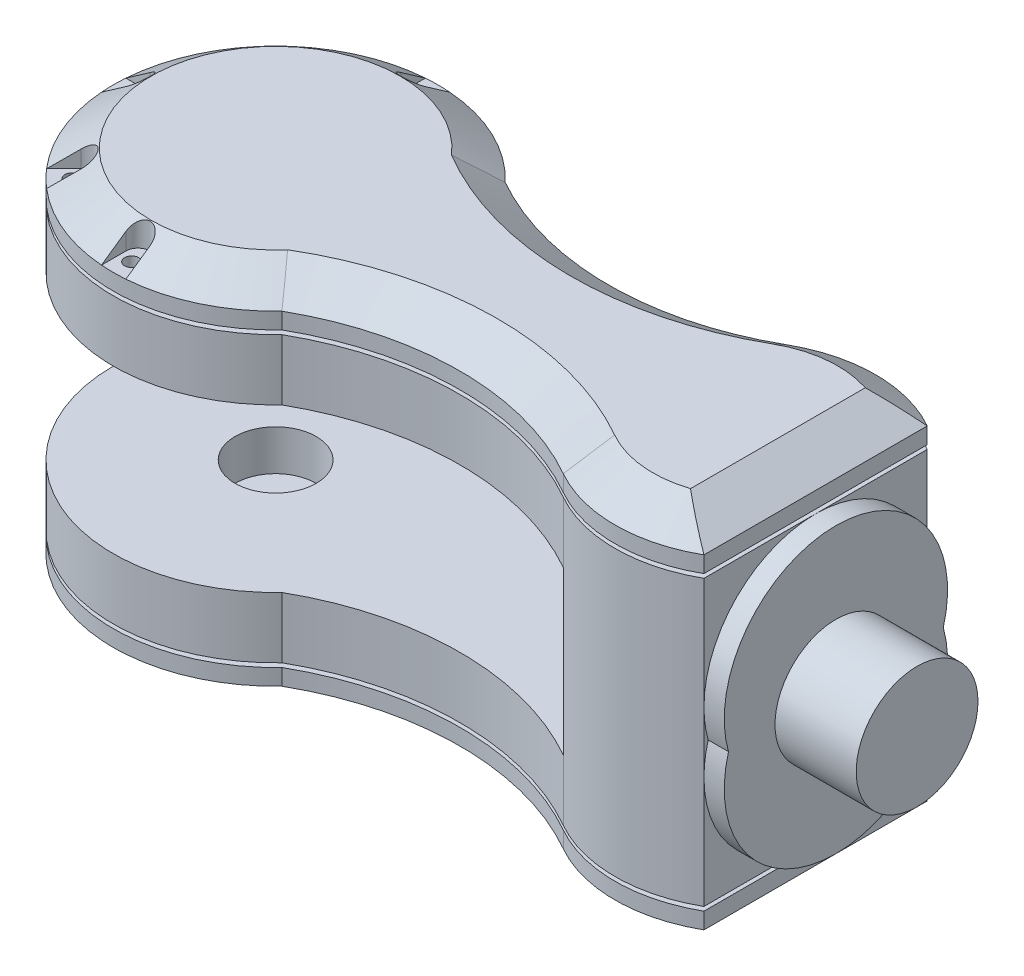
SolidWorks part; units mm, degrees
ref_plane "Front Plane" through (0, 0, 0) normal (1, 0, 0) x (0, 1, 0)
ref_plane "Top Plane" through (0, 0, 0) normal (0, 0, 1) x (0, 1, 0)
ref_plane "Right Plane" through (0, 0, 0) normal (0, 1, 0) x (-1, 0, 0)
sketch "Sketch1" plane through (0, 0, 0) normal (1, 0, 0) x (0, 1, 0)
  circle A0 centre (0, 0) radius 27.5
  dimension "D1" = 55
extrude "Boss-Extrude1" add sketch "Sketch1" against normal blind 5
ref_plane "Plane1" through (0, 27.5, 0) normal (0, 1, 0) x (-1, 0, 0)
sketch "Sketch3" plane through (0, 27.5, 0) normal (0, 1, 0) x (-1, 0, 0)
  line L0 (5, 0) -> (28, 0) construction
  line L1 (5, -27.5) -> (5, 27.5) construction
  line L2 (5, 27.5) -> (5, -27.5)
  arc A0 (5, 27.5) -> (39.6509, 27.5) centre (22.3254, -2.911) cw
  arc A1 (39.6509, 27.5) -> (108.9526, 27.5) centre (74.3017, 88.322) ccw
  arc A2 (5, -27.5) -> (39.6509, -27.5) centre (22.3254, 2.911) ccw
  arc A3 (39.6509, -27.5) -> (108.9526, -27.5) centre (74.3017, -88.322) cw
  arc A4 (108.9526, -27.5) -> (108.9526, 27.5) centre (138, 0) ccw
  dimension "D2" = 70
  dimension "D3" = 80
  dimension "D5" = 35
  dimension "D1" = 23
  dimension "D4" = 110
extrude "Boss-Extrude2" add sketch "Sketch3" along normal blind 15 separate body
sketch "Sketch7" plane through (0, 42.5, 0) normal (0, 1, 0) x (-1, 0, 0)
  line L2 (7.5, 26.0106) -> (7.5, -26.0106)
  line L3 (7.5, 26.0106) -> (7.5, -26.0106)
  arc A10 (38.4133, 25.3278) -> (7.5, 26.0106) centre (22.3254, -2.911) ccw
  arc A11 (7.5, -26.0106) -> (38.4133, -25.3278) centre (22.3254, 2.911) ccw
  arc A12 (110.5204, -25.5171) -> (38.4133, -25.3278) centre (74.3017, -88.322) ccw
  arc A13 (110.5204, -25.5171) -> (110.5204, 25.5171) centre (138, 0) ccw
  arc A14 (38.4133, 25.3278) -> (110.5204, 25.5171) centre (74.3017, 88.322) ccw
  arc A15 (38.4133, 25.3278) -> (7.5, 26.0106) centre (22.3254, -2.911) ccw
  arc A16 (7.5, -26.0106) -> (38.4133, -25.3278) centre (22.3254, 2.911) ccw
  arc A17 (110.5204, -25.5171) -> (38.4133, -25.3278) centre (74.3017, -88.322) ccw
  arc A18 (110.5204, -25.5171) -> (110.5204, 25.5171) centre (138, 0) ccw
  arc A19 (38.4133, 25.3278) -> (110.5204, 25.5171) centre (74.3017, 88.322) ccw
  dimension "D1" = 2.5
extrude "Boss-Extrude10" add sketch "Sketch7" along normal blind 1 contours A15 L3 A16 A17 A18 A19
sketch "Sketch18" plane through (0, 43.5, 0) normal (0, 1, 0) x (-1, 0, 0)
  line L1 (5, 27.5) -> (5, -27.5)
  line L2 (5, 27.5) -> (5, -27.5)
  arc A5 (39.6509, 27.5) -> (5, 27.5) centre (22.3254, -2.911) ccw
  arc A6 (5, -27.5) -> (39.6509, -27.5) centre (22.3254, 2.911) ccw
  arc A7 (108.9526, -27.5) -> (39.6509, -27.5) centre (74.3017, -88.322) ccw
  arc A8 (108.9526, -27.5) -> (108.9526, 27.5) centre (138, 0) ccw
  arc A9 (39.6509, 27.5) -> (108.9526, 27.5) centre (74.3017, 88.322) ccw
  arc A10 (39.6509, 27.5) -> (5, 27.5) centre (22.3254, -2.911) ccw
  arc A11 (5, -27.5) -> (39.6509, -27.5) centre (22.3254, 2.911) ccw
  arc A12 (108.9526, -27.5) -> (39.6509, -27.5) centre (74.3017, -88.322) ccw
  arc A13 (108.9526, -27.5) -> (108.9526, 27.5) centre (138, 0) ccw
  arc A14 (39.6509, 27.5) -> (108.9526, 27.5) centre (74.3017, 88.322) ccw
  dimension "D1" = 0
extrude "Boss-Extrude14" add sketch "Sketch18" along normal blind 4
sketch "Sketch19" plane through (0, 47.5, 0) normal (0, 1, 0) x (-1, 0, 0)
  line L1 (5, 27.5) -> (5, -27.5)
  line L2 (5, 27.5) -> (5, -27.5)
  arc A5 (39.6509, 27.5) -> (108.9526, 27.5) centre (74.3017, 88.322) ccw
  arc A6 (39.6509, 27.5) -> (5, 27.5) centre (22.3254, -2.911) ccw
  arc A7 (5, -27.5) -> (39.6509, -27.5) centre (22.3254, 2.911) ccw
  arc A8 (108.9526, -27.5) -> (39.6509, -27.5) centre (74.3017, -88.322) ccw
  arc A9 (108.9526, -27.5) -> (108.9526, 27.5) centre (138, 0) ccw
  arc A10 (39.6509, 27.5) -> (108.9526, 27.5) centre (74.3017, 88.322) ccw
  arc A11 (39.6509, 27.5) -> (5, 27.5) centre (22.3254, -2.911) ccw
  arc A12 (5, -27.5) -> (39.6509, -27.5) centre (22.3254, 2.911) ccw
  arc A13 (108.9526, -27.5) -> (39.6509, -27.5) centre (74.3017, -88.322) ccw
  arc A14 (108.9526, -27.5) -> (108.9526, 27.5) centre (138, 0) ccw
  dimension "D1" = 0
extrude "Boss-Extrude15" add sketch "Sketch19" along normal blind 6.5 draft 55
sketch "Sketch20" plane through (0, 54, 0) normal (0, 1, 0) x (-1, 0, 0)
  line L0 (5, 0) -> (178, 0) construction
  line L1 (5, 27.5) -> (5, -27.5) construction
  line L2 (177.8873, 3) -> (171.8873, 3)
  line L3 (177.8873, -3) -> (171.8873, -3)
  arc A0 (108.9526, -27.5) -> (108.9526, 27.5) centre (138, 0) ccw construction
  arc A1 (171.8873, 3) -> (171.8873, -3) centre (171.8873, 0) ccw
  arc A2 (177.8873, 3) -> (177.8873, -3) centre (173.8873, 0) cw
  dimension "D3" = 3
  dimension "D4" = 5
  dimension "D1" = 3
  dimension "D2" = 6
extrude "Cut-Extrude1" cut sketch "Sketch20" against normal blind 6.5
sketch "Sketch21" plane through (0, 47.5, 0) normal (0, 1, 0) x (-1, 0, 0)
  line L0 (178, 0) -> (168.8873, 0) construction
  arc A0 (177.8873, -3) -> (177.8873, 3) centre (138, 0) ccw construction
  arc A1 (171.8873, 3) -> (171.8873, -3) centre (171.8873, 0) ccw construction
  circle A2 centre (173.4437, 0) radius 1.75
  dimension "D1" = 3.5
extrude "Cut-Extrude2" cut sketch "Sketch21" against normal blind 5
pattern_circular "CirPattern1" count 3 every 45 about axis through (-138, 0, 0) along (0, 1, 0) of "Cut-Extrude2", "Cut-Extrude1"
sketch "Sketch23" plane through (0, 27.5, 0) normal (0, -1, 0) x (1, 0, 0)
  line L0 (-39.6509, 27.5) -> (-39.6509, -27.5)
  line L1 (-5, -27.5) -> (-5, 27.5)
  line L2 (-5, -27.5) -> (-5, 27.5)
  arc A5 (-5, 27.5) -> (-39.6509, 27.5) centre (-22.3254, -2.911) ccw
  arc A6 (-108.9526, 27.5) -> (-39.6509, 27.5) centre (-74.3017, 88.322) ccw
  arc A7 (-108.9526, 27.5) -> (-108.9526, -27.5) centre (-138, 0) ccw
  arc A8 (-39.6509, -27.5) -> (-108.9526, -27.5) centre (-74.3017, -88.322) ccw
  arc A9 (-39.6509, -27.5) -> (-5, -27.5) centre (-22.3254, 2.911) ccw
  arc A10 (-5, 27.5) -> (-39.6509, 27.5) centre (-22.3254, -2.911) ccw
  arc A14 (-39.6509, -27.5) -> (-5, -27.5) centre (-22.3254, 2.911) ccw
  dimension "D1" = 0
extrude "Boss-Extrude16" add sketch "Sketch23" along normal blind 40
ref_plane "Plane2" through (0, 7.5, 0) normal (0, -1, 0) x (-1, 0, 0)
mirror "Mirror1" about plane through (0, 7.5, 0) normal (0, -1, 0) of bodies 119
sketch "Sketch25" plane through (0, 0, 0) normal (1, 0, 0) x (0, 1, 0)
  line L0 (7.5, 26.4575) -> (7.5, -26.4575) construction
  circle A0 centre (7.5, 0) radius 15
  dimension "D1" = 30
extrude "Boss-Extrude17" add sketch "Sketch25" along normal blind 20
sketch "Sketch26" plane through (0, 27.5, 0) normal (0, -1, 0) x (1, 0, 0)
  circle A0 centre (-138, 0) radius 10
  dimension "D1" = 20
extrude "Cut-Extrude3" cut sketch "Sketch26" against normal blind 10
mirror "Mirror2" about plane through (0, 7.5, 0) normal (0, -1, 0) of "Cut-Extrude3"
